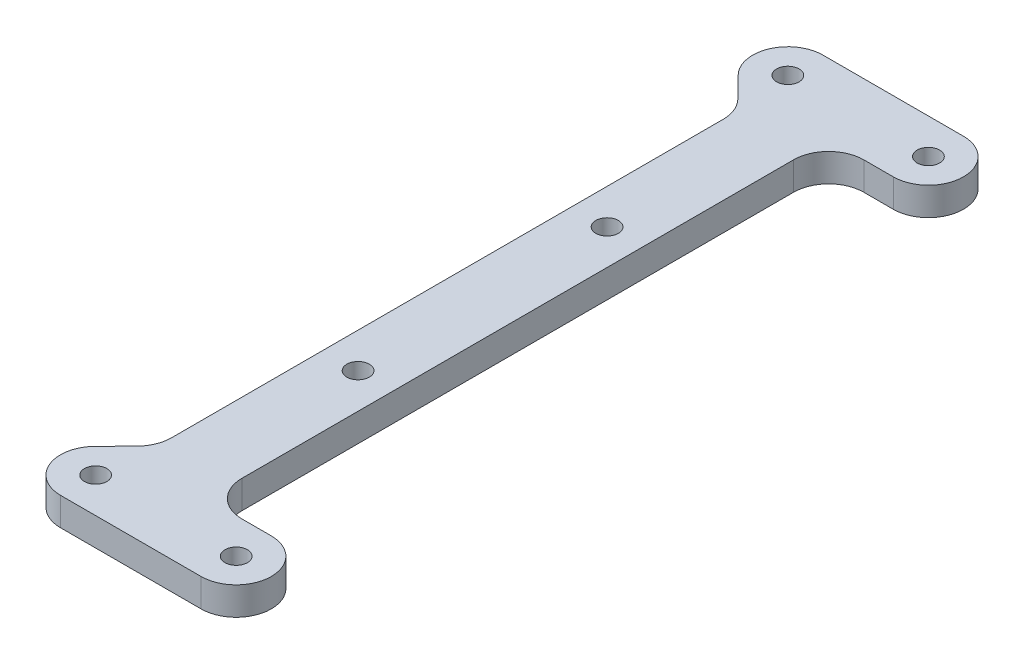
SolidWorks part; units mm, degrees
ref_plane "Спереди" through (0, 0, 0) normal (0, 0, 1) x (1, 0, 0)
ref_plane "Сверху" through (0, 0, 0) normal (0, 1, 0) x (1, 0, 0)
ref_plane "Справа" through (0, 0, 0) normal (1, 0, 0) x (0, 0, -1)
sketch "Sketch1" plane through (0, 0, 0) normal (0, 1, 0) x (1, 0, 0)
  line L0 (0, 0) -> (28.9283, 0) construction
  line L1 (-10, 49.25) -> (10, 49.25) construction
  line L2 (-10, 54.25) -> (10, 54.25)
  line L3 (0, 49.25) -> (0, -49.25) construction
  line L4 (-9.19, 39.25) -> (-9.19, -39.25)
  line L5 (-10, 44.25) -> (10, 44.25)
  line L6 (-4.19, -17.715) -> (-4.19, 17.715) construction
  line L7 (0.81, 39.25) -> (0.81, -39.25)
  line L8 (-10, -49.25) -> (10, -49.25) construction
  line L9 (-10, -54.25) -> (10, -54.25)
  line L10 (-10, -44.25) -> (10, -44.25)
  line L11 (-10.6257, 42.7566) -> (-13.5643, 45.7434)
  line L12 (-10.6257, -42.7566) -> (-13.5643, -45.7434)
  circle A0 centre (-10, 49.25) radius 1.6
  circle A1 centre (10, 49.25) radius 1.6
  circle A2 centre (10, -49.25) radius 1.6
  circle A3 centre (-10, -49.25) radius 1.6
  circle A4 centre (21.86, 44.45) radius 1.6
  circle A5 centre (21.86, -44.45) radius 1.6
  arc A6 (-10, 54.25) -> (-10, 44.25) centre (-10, 49.25) ccw
  arc A7 (10, 44.25) -> (10, 54.25) centre (10, 49.25) ccw
  circle A8 centre (-4.19, 17.715) radius 1.6
  circle A9 centre (-4.19, -17.715) radius 1.6
  arc A10 (-10, -54.25) -> (-10, -44.25) centre (-10, -49.25) cw
  arc A11 (10, -44.25) -> (10, -54.25) centre (10, -49.25) cw
  arc A12 (0.81, 39.25) -> (5.81, 44.25) centre (5.81, 39.25) cw
  arc A13 (-9.19, 39.25) -> (-10.6257, 42.7566) centre (-14.19, 39.25) ccw
  arc A14 (0.81, -39.25) -> (5.81, -44.25) centre (5.81, -39.25) ccw
  arc A15 (-9.19, -39.25) -> (-10.6257, -42.7566) centre (-14.19, -39.25) cw
  point P14 (0, 49.25)
  point P25 (0, -49.25)
  point P39 (0, 37.6143)
  point P41 (0, 0)
  point P42 (0, 40.3311)
  point P43 (4.9797, 45.25)
  point P44 (-8.19, 41.0987)
  point P45 (0, 0)
  dimension "D1" = 3.2
  dimension "D2" = 98.5
  dimension "D3" = 20
  dimension "D4" = 88.9
  dimension "D5" = 11.86
  dimension "D6" = 10
  dimension "D7" = 35.43
  dimension "D8" = 5.81
  dimension "D9" = 10
extrude "Boss-Extrude1" add sketch "Sketch1" along normal blind 4
equation "\"D9@Sketch1\"=\"D6@Sketch1\""
